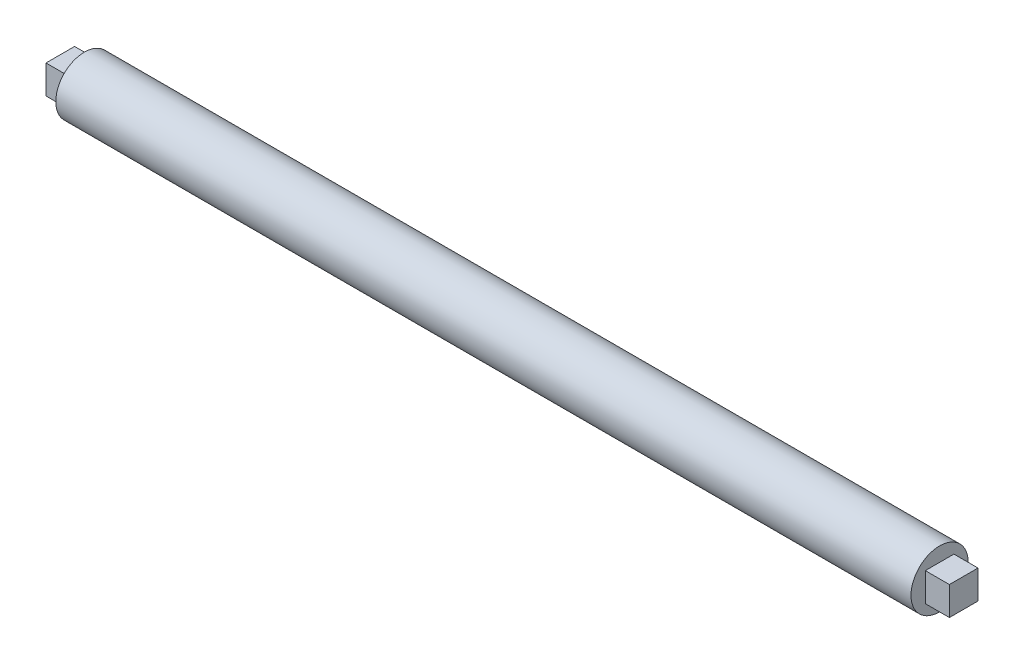
SolidWorks part; units mm, degrees
ref_plane "Plan de face" through (0, 0, 0) normal (0, 0, 1) x (1, 0, 0)
ref_plane "Plan de dessus" through (0, 0, 0) normal (0, 1, 0) x (1, 0, 0)
ref_plane "Plan de droite" through (0, 0, 0) normal (1, 0, 0) x (0, 0, -1)
sketch "Esquisse1" plane through (0, 0, 0) normal (0, 1, 0) x (1, 0, 0)
  line L0 (0, 0) -> (0, 4.75)
  line L1 (0, 4.75) -> (142, 4.75)
  line L2 (142, 4.75) -> (142, 0)
  line L30 (0, 0) -> (16.75, 0)
  line L31 (24.75, 0) -> (117.25, 0)
  line L32 (125.25, 0) -> (142, 0)
  line L33 (16.75, 0) -> (24.75, 0)
  line L34 (117.25, 0) -> (125.25, 0)
  dimension "D1" = 142
  dimension "D8" = 4.75
revolve "Révolution1" add sketch "Esquisse1" angle 360 about L1
sketch "Esquisse5" plane through (142, 0, 0) normal (1, 0, 0) x (0, 0, -1)
  line L0 (2.375, 2.375) -> (2.375, -2.375)
  line L9 (2.375, 2.375) -> (7.125, 2.375)
  line L10 (7.125, 2.375) -> (7.125, -2.375)
  line L11 (7.125, -2.375) -> (2.375, -2.375)
extrude "Boss.-Extru.3" add sketch "Esquisse5" along normal blind 4
sketch "Esquisse6" plane through (0, 0, 0) normal (-1, 0, 0) x (0, 0, 1)
  line L8 (-4.75, 2.375) -> (-7.125, 2.375)
  line L9 (-7.125, 2.375) -> (-7.125, -2.375)
  line L10 (-7.125, -2.375) -> (-2.375, -2.375)
  line L11 (-2.375, -2.375) -> (-2.375, 2.375)
  line L12 (-2.375, 2.375) -> (-4.75, 2.375)
extrude "Boss.-Extru.4" add sketch "Esquisse6" along normal blind 4
